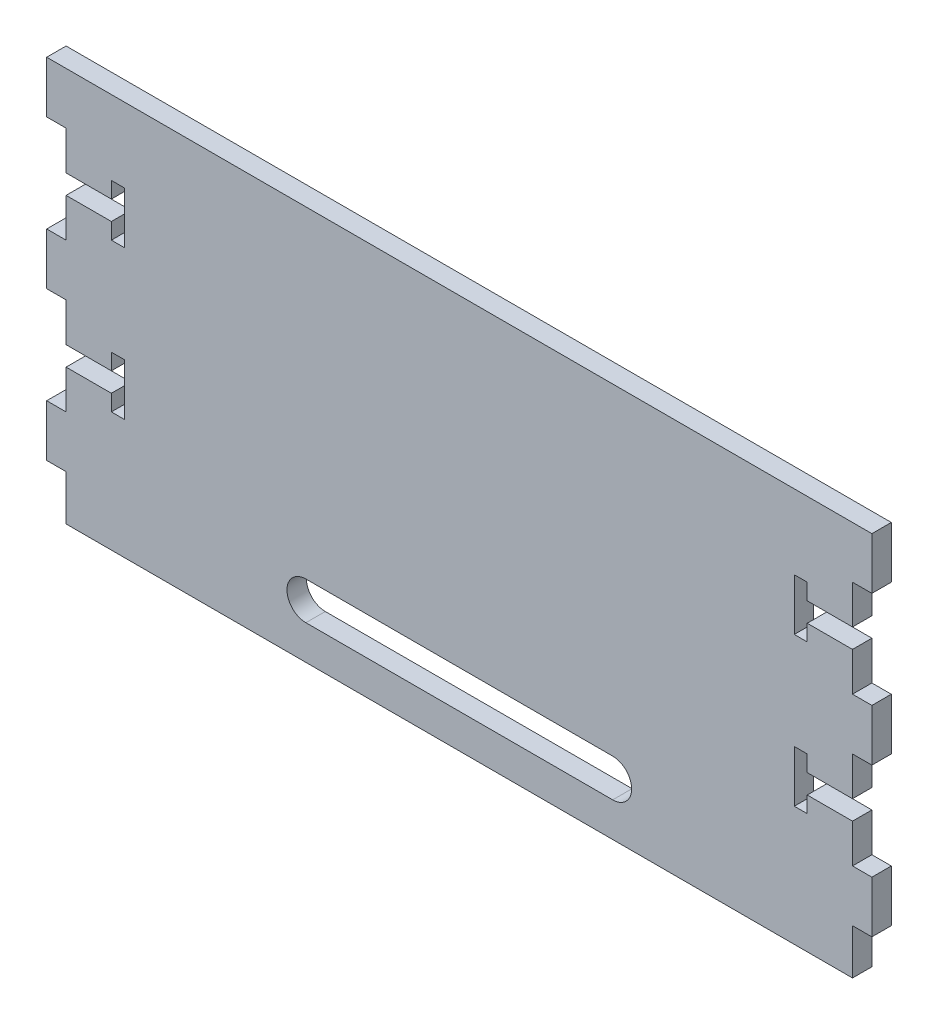
SolidWorks part; units mm, degrees
material "Balsa"
ref_plane "Front Plane" through (0, 0, 0) normal (0, 0, 1) x (1, 0, 0)
ref_plane "Top Plane" through (0, 0, 0) normal (0, 1, 0) x (1, 0, 0)
ref_plane "Right Plane" through (0, 0, 0) normal (1, 0, 0) x (0, 0, -1)
sketch "Sketch1" plane through (0, 0, 0) normal (0, 0, 1) x (1, 0, 0)
  line L5 (-60.8, -30.5024) -> (60.8, -30.5024)
  line L6 (-60.8, -30.5024) -> (-60.8, 30.5024)
  line L7 (-60.8, 30.5024) -> (60.8, 30.5024)
  line L8 (60.8, -30.5024) -> (60.8, 30.5024)
  line L9 (-60.8, -30.5024) -> (60.8, 30.5024) construction
  line L10 (-60.8, 30.5024) -> (60.8, -30.5024) construction
  point P0 (0, 0)
  dimension "D1" = 121.6
extrude "Boss-Extrude1" add sketch "Sketch1" along normal blind 3
sketch "Sketch3" plane through (60.8, 0, 0) normal (1, 0, 0) x (0, 0, -1)
  line L0 (0, -30.5024) -> (0, 30.5024) construction
  line L1 (-3, -30.5024) -> (-3, 30.5024) construction
  line L2 (-3, 7.5024) -> (-3, -0.4976)
  line L3 (0, 7.5024) -> (-3, 7.5024)
  line L4 (0, -0.4976) -> (0, 7.5024)
  line L5 (-3, -0.4976) -> (0, -0.4976)
  line L6 (-3, -15.4976) -> (-3, -23.4976)
  line L7 (0, -15.4976) -> (-3, -15.4976)
  line L8 (0, 30.5024) -> (-3, 30.5024)
  line L9 (0, 22.5024) -> (0, 30.5024)
  line L10 (-3, 22.5024) -> (0, 22.5024)
  line L11 (-3, 30.5024) -> (-3, 22.5024)
  line L12 (0, -23.4976) -> (0, -15.4976)
  line L13 (-3, -23.4976) -> (0, -23.4976)
  line L14 (-3, 30.5024) -> (-3, 7.5024) construction
  line M15 (0, -30.5024) -> (0, 30.5024)
  line M16 (0, 30.5024) -> (-3, 30.5024)
  line M17 (-3, 30.5024) -> (-3, -30.5024)
  dimension "D1" = 8
  dimension "D3" = 23
  dimension "D2" = 3
extrude "Boss-Extrude2" add sketch "Sketch3" along normal blind 3 contours L10 M17 M15 M16 | L5 L3 M17 M15 | L13 L7 M17 M15
mirror "Mirror1" about plane through (0, 0, 0) normal (1, 0, 0) of "Boss-Extrude2"
sketch "Sketch4" plane through (0, 0, 0) normal (0, 0, 1) x (1, 0, 0)
  line L0 (63.8, 3.5024) -> (-63.8, 3.5024) construction
  line L3 (-63.8, -0.4976) -> (-63.8, 7.5024) construction
  point P4 (-63.8, 3.5024)
sketch "Sketch5" plane through (0, 0, 0) normal (0, 0, -1) x (-1, 0, 0)
  line L0 (-60.8, 15.0024) -> (0, 15.0024) construction
  line L1 (-60.8, 7.5024) -> (-60.8, 22.5024) construction
  line L2 (-60.8, 15.0024) -> (-63.8, 15.0024) construction
  line L3 (0, 0) -> (0, 15.0024) construction
  line L9 (-53.8, 16.5024) -> (-60.8, 16.5024)
  line L10 (-53.8, 16.5024) -> (-53.8, 13.5024)
  line L11 (-53.8, 13.5024) -> (-60.8, 13.5024)
  line L12 (-60.8, 16.5024) -> (-60.8, 13.5024)
  line L13 (-53.8, 16.5024) -> (-60.8, 13.5024) construction
  line L14 (-53.8, 13.5024) -> (-60.8, 16.5024) construction
  line L15 (-51.8, 19.0024) -> (-53.8, 19.0024)
  line L16 (-51.8, 19.0024) -> (-51.8, 11.0024)
  line L17 (-51.8, 11.0024) -> (-53.8, 11.0024)
  line L18 (-53.8, 19.0024) -> (-53.8, 11.0024)
  line L19 (-51.8, 19.0024) -> (-53.8, 11.0024) construction
  line L20 (-51.8, 11.0024) -> (-53.8, 19.0024) construction
  point P7 (-57.3, 15.0024)
  point P13 (-52.8, 15.0024)
  line M26 (-60.8, 22.5024) -> (-60.8, 7.5024)
  dimension "D1" = 9
  dimension "D2" = 8
  dimension "D3" = 3
  dimension "D4" = 2
extrude "Cut-Extrude1" cut sketch "Sketch5" against normal through all contours L11 L10 L9 M26 | L15 L18 L10 L17 L16
mirror "Mirror2" about plane through (0, 0, 0) normal (1, 0, 0) of "Cut-Extrude1"
ref_plane "Plane2" through (0, 3.5024, 0) normal (0, -1, 0) x (-1, 0, 0)
mirror "Mirror3" about plane through (0, 3.5024, 0) normal (0, -1, 0) of "Mirror2", "Cut-Extrude1"
sketch "Sketch6" plane through (0, 0, 0) normal (0, 0, -1) x (-1, 0, 0)
  line L0 (-23.7213, -22.2576) -> (23.7213, -22.2576) construction
  line L1 (-23.7213, -19.3303) -> (23.7213, -19.3303)
  line L2 (-23.7213, -25.185) -> (23.7213, -25.185)
  arc A0 (-23.7213, -19.3303) -> (-23.7213, -25.185) centre (-23.7213, -22.2576) ccw
  arc A1 (23.7213, -25.185) -> (23.7213, -19.3303) centre (23.7213, -22.2576) ccw
  point P2 (0, -22.2576)
  point P7 (0, -24.0746)
extrude "VelcroHole" cut sketch "Sketch6" against normal through all both and the other way through all
